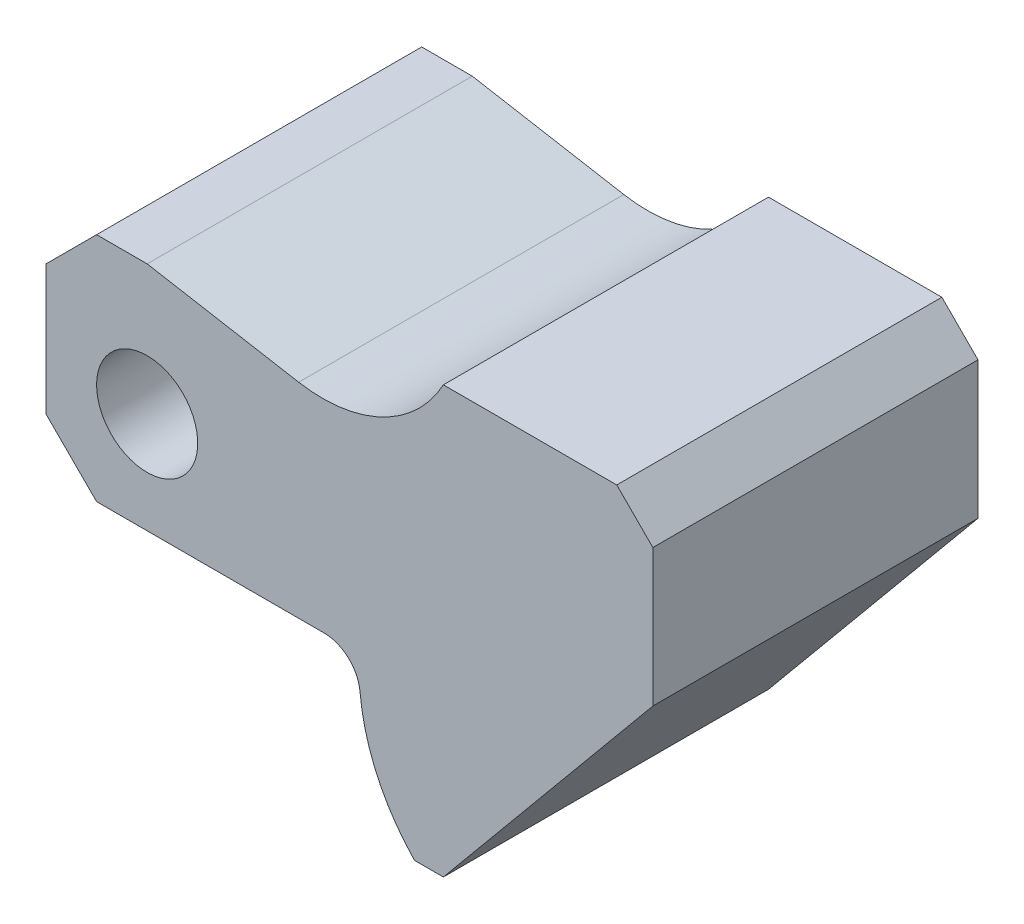
SolidWorks part; units mm, degrees
material "AISI 1020"
ref_plane "Plan de face" through (0, 0, 0) normal (0, 0, 1) x (1, 0, 0)
ref_plane "Plan de dessus" through (0, 0, 0) normal (0, 1, 0) x (1, 0, 0)
ref_plane "Plan de droite" through (0, 0, 0) normal (1, 0, 0) x (0, 0, -1)
sketch "Esquisse1" plane through (0, 0, 0) normal (0, 0, 1) x (1, 0, 0)
  line L0 (33.5026, 1.4077) -> (57.5026, 1.4077)
  line L1 (57.5026, 1.4077) -> (62.5026, -3.5923)
  line L2 (62.5026, -3.5923) -> (62.5026, -22.5923)
  line L3 (62.5026, -22.5923) -> (33.5026, -57.5923)
  line L4 (33.5026, -57.5923) -> (29.5026, -57.5923)
  line L6 (16.9843, -36.5923) -> (-14.4974, -36.5923)
  line L7 (-14.4974, -36.5923) -> (-21.4974, -29.5923)
  line L8 (-21.4974, -29.5923) -> (-21.4974, -11.5923)
  line L9 (-21.4974, -11.5923) -> (-14.4974, -4.5923)
  line L12 (-14.4974, -4.5923) -> (-7.4974, -4.5923)
  line L18 (-7.4974, -4.5923) -> (13.4771, -8.2907)
  arc A1 (21.9628, -41.1294) -> (16.9843, -36.5923) centre (16.9843, -41.5923) ccw
  arc A2 (33.5026, 1.4077) -> (13.4771, -8.2907) centre (16.7764, 10.4206) cw
  arc A3 (29.5026, -57.5923) -> (21.9628, -41.1294) centre (49.2454, -38.5923) cw
  circle A4 centre (-7.4974, -22.5923) radius 7
  point P17 (27.1901, -38.5923)
  dimension "D15" = 5
  dimension "D16" = 190
  dimension "D17" = 19
  dimension "D18" = 14
  dimension "D1" = 29
  dimension "D2" = 24
  dimension "D3" = 59
  dimension "D4" = 5
  dimension "D5" = 7
  dimension "D6" = 32
  dimension "D7" = 7
  dimension "D8" = 19
  dimension "D10" = 135
  dimension "D11" = 84
  dimension "D12" = 14
  dimension "D13" = 135
  dimension "D14" = 29
  dimension "D19" = 14
  dimension "D20" = 135
  dimension "D21" = 0
  dimension "D22" = 4
extrude "Boss.-Extru.2" add sketch "Esquisse1" along normal blind 45
